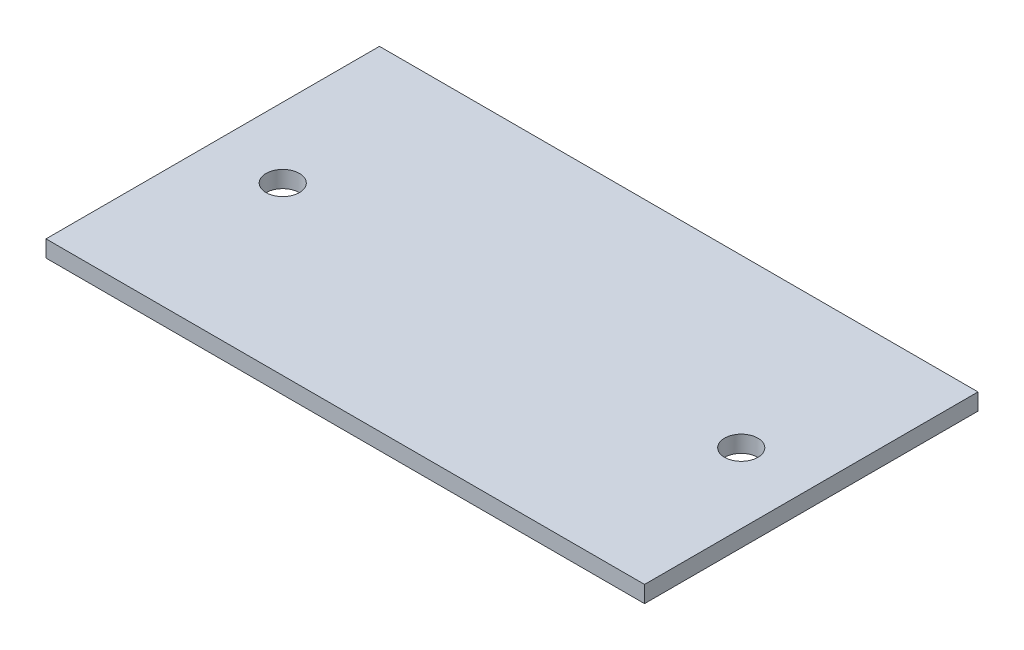
SolidWorks part; units mm, degrees
ref_plane "Plano frontal" through (0, 0, 0) normal (0, 0, 1) x (1, 0, 0)
ref_plane "Plano superior" through (0, 0, 0) normal (0, 1, 0) x (1, 0, 0)
ref_plane "Plano direito" through (0, 0, 0) normal (1, 0, 0) x (0, 0, -1)
sketch "Esboço1" plane through (0, 0, 0) normal (0, 1, 0) x (1, 0, 0)
  line L1 (-17.95, -10) -> (17.95, -10)
  line L2 (-17.95, -10) -> (-17.95, 10)
  line L3 (-17.95, 10) -> (17.95, 10)
  line L4 (17.95, -10) -> (17.95, 10)
  line L5 (-17.95, -10) -> (17.95, 10) construction
  line L6 (-17.95, 10) -> (17.95, -10) construction
  point P0 (0, 0)
  dimension "D1" = 20
  dimension "D2" = 35.9
extrude "Ressalto-extrusão1" add sketch "Esboço1" along normal blind 1
sketch "Esboço2" plane through (0, 1, 0) normal (0, 1, 0) x (1, 0, 0)
  circle A0 centre (13.75, 0) radius 1
  circle A1 centre (-13.75, 0) radius 1
  dimension "D1" = 13.75
  dimension "D2" = 13.75
extrude "Corte-extrusão1" cut sketch "Esboço2" against normal up to next
